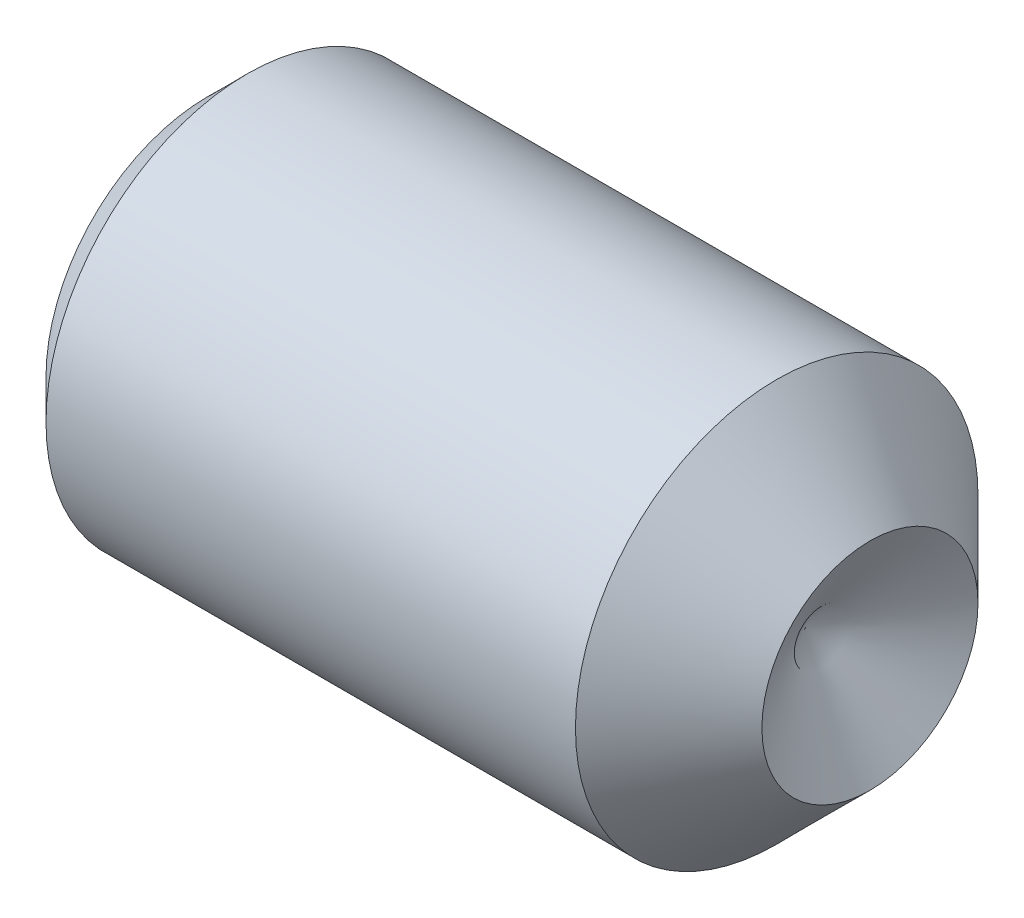
SolidWorks part; units mm, degrees
other "Defeature"
material "Alloy Steel"
ref_plane "Plane1" through (0, 0, 0) normal (0, 0, 1) x (1, 0, 0)
ref_plane "Plane2" through (0, 0, 0) normal (0, 1, 0) x (1, 0, 0)
ref_plane "Plane3" through (0, 0, 0) normal (1, 0, 0) x (0, 0, -1)
sketch "BodySke" plane through (0, 0, 0) normal (0, 0, 1) x (1, 0, 0)
  line L0 (0, 0) -> (0, 1.9406)
  line L1 (0, 1.9406) -> (0.4724, 2.413)
  line L2 (0.4724, 2.413) -> (6.8199, 2.413)
  line L3 (6.8199, 2.413) -> (7.9375, 1.2954)
  line L4 (7.1591, 0) -> (0, 0)
  line L5 (-12.7, 0) -> (88.9, 0) construction
  line L6 (7.1591, 0) -> (7.9375, 1.2954)
  line L7 (7.9375, 1.2954) -> (7.9375, 10.8204) construction
  line L8 (0, -1.9406) -> (0.4724, -2.413) construction
  line L9 (7.1591, 0) -> (7.9375, -1.2954) construction
  line L10 (6.8199, -2.413) -> (7.9375, -1.2954) construction
  line L11 (0.7925, 15.875) -> (0.7925, -3.175) construction
  dimension "Length" = 7.9375
  dimension "Diameter" = 4.826
  dimension "Drive_ch_ang" = 45
  dimension "Minor_dia" = 3.8811
  dimension "Cup_nose_ang" = 45
  dimension "Cup_ang" = 118
  dimension "Cup_dia" = 2.5908
  dimension "Advance" = 0.7925
revolve "BaseBody" add sketch "BodySke" angle 360 about L5
cosmetic thread "ThreadCosmetic" parameters "Thread_minor"=3.8811
sketch "Sketch2" plane through (0, 0, 0) normal (-1, 0, 0) x (0, 0, 1)
  line L0 (0.687, 1.19) -> (-0.687, 1.19)
  line L1 (-0.687, 1.19) -> (-1.3741, 0)
  line L2 (0.687, 1.19) -> (1.3741, 0)
  line L3 (0.687, -1.19) -> (1.3741, 0)
  line L4 (0.687, -1.19) -> (-0.687, -1.19)
  line L5 (-0.687, -1.19) -> (-1.3741, 0)
  dimension "Hex_size" = 2.38
  dimension "D2" = 1.19
  dimension "D3" = 1.19
extrude "Hex" cut sketch "Sketch2" against normal blind 2.54
sketch "Sketch4" plane through (0, 4.7709, -0.5249) normal (-1, 0, 0) x (0, 0, 1)
  line L0 (0.5249, -4.7709) -> (1.9854, -4.7709)
  line L1 (0.5249, -4.7709) -> (6.6732, -1.2211) construction
  line L2 (0.5249, -4.7709) -> (1.2551, -3.506)
  line L3 (1.7258, -4.4441) -> (1.9182, -4.333)
  line L4 (1.4083, -3.8942) -> (1.6007, -3.7831)
  arc A0 (1.7258, -4.4441) -> (1.4083, -3.8942) centre (0.5249, -4.7709) ccw
  arc A1 (1.9854, -4.7709) -> (1.9182, -4.333) centre (0.5249, -4.7709) ccw
  arc A2 (1.2551, -3.506) -> (1.6007, -3.7831) centre (0.5249, -4.7709) cw
  circle A3 centre (0.5249, -4.7709) radius 1.2446 construction
  circle A4 centre (0.5249, -4.7709) radius 1.4605 construction
  dimension "D1" = 30
  dimension "Spline_n_dim" = 2.4892
  dimension "Spline_m_dim" = 2.921
  dimension "Spline_a_dim" = 60
  dimension "D3" = 0.3175
  dimension "Spline_p_dim" = 0.635
extrude "Spline" [suppressed] cut sketch "Sketch4" against normal blind 2.032
pattern_circular "CirPattern1" [suppressed] count 6 every 60 about axis through (-12.7, 0, 0) along (1, 0, 0)
sketch "ThdSchSke" plane through (0, 0, 0) normal (0, 0, 1) x (1, 0, 0)
  line L0 (0.4724, -1.9406) -> (0.1416, -2.413)
  line L1 (0.4724, -1.9406) -> (0.8032, -2.413)
  line L2 (0.8032, -2.413) -> (0.8032, -3.0162)
  line L3 (-3.175, 0) -> (5.1513, 0) construction
  line L4 (0.4724, 2.413) -> (0.4724, -2.413) construction
  line L5 (0.8032, -3.0162) -> (0.1416, -3.0162)
  line L6 (0.1416, -3.0162) -> (0.1416, -2.413)
  dimension "Thread_minor" = 3.8811
  dimension "Diameter" = 4.826
  dimension "SideAngle" = 55
  dimension "VeeAngle" = 70
  dimension "Overcut" = 6.0325
revolve "ThreadSchematic" [suppressed] cut sketch "ThdSchSke" angle 360 about L3
pattern_linear "ThdSchPat" [suppressed]
equation "\"D2@Sketch2\" = \"Hex_size@Sketch2\" / 2"
equation "\"D3@Sketch2\" = \"Hex_size@Sketch2\" / 2"
equation "\"Thread_minor@ThreadCosmetic\" = \"Minor_dia@BodySke\""
equation "\"D1@Sketch4\" = \"Spline_a_dim@Sketch4\" / 2"
equation "\"D3@Sketch4\" = \"Spline_p_dim@Sketch4\" / 2"
equation "\"D2@CirPattern1\" = \"Spline_a_dim@Sketch4\""
equation "\"Num_teeth@CirPattern1\" = 360 / \"D2@CirPattern1\""
equation "\"Thread_minor@ThdSchSke\" = \"Thread_minor@ThreadCosmetic\""
equation "\"Diameter@ThdSchSke\" = \"Diameter@BodySke\""
equation "\"Overcut@ThdSchSke\" = \"Diameter@BodySke\" * 1.25"
equation "\"Num_threads@ThdSchPat\" = int( (\"Length@BodySke\" - ( ( ( \"Diameter@BodySke\" - \"Minor_dia@BodySke\" ) * 0.5 ) / tan( \"Drive_ch_ang@BodySke\" * 0.017453292 ) ) - ( ( ( \"Diameter@BodySke\" - \"Cup_dia@BodySke\" ) * 0.5 ) * tan( \"Cup_nose_ang@BodySke\" * 0.017453292 ) ) ) / \"Advance@BodySke\" + 0.999 )  + 1"
equation "\"Advance@ThdSchPat\" = (\"Length@BodySke\" - ( ( ( \"Diameter@BodySke\" - \"Minor_dia@BodySke\" ) * 0.5 ) / tan( \"Drive_ch_ang@BodySke\" * 0.017453292 ) ) - ( ( ( \"Diameter@BodySke\" - \"Cup_dia@BodySke\" ) * 0.5 ) * tan( \"Cup_nose_ang@BodySke\" * 0.017453292 ) ) ) /  (\"Num_threads@ThdSchPat\" - 1) 'relax it"
equation "' \"Num_threads@ThdSchPat\" = \"Num_threads@ThdSchPat\" - sgn( \"Num_threads@ThdSchPat\" - 1) '---chamfered tips only---"
